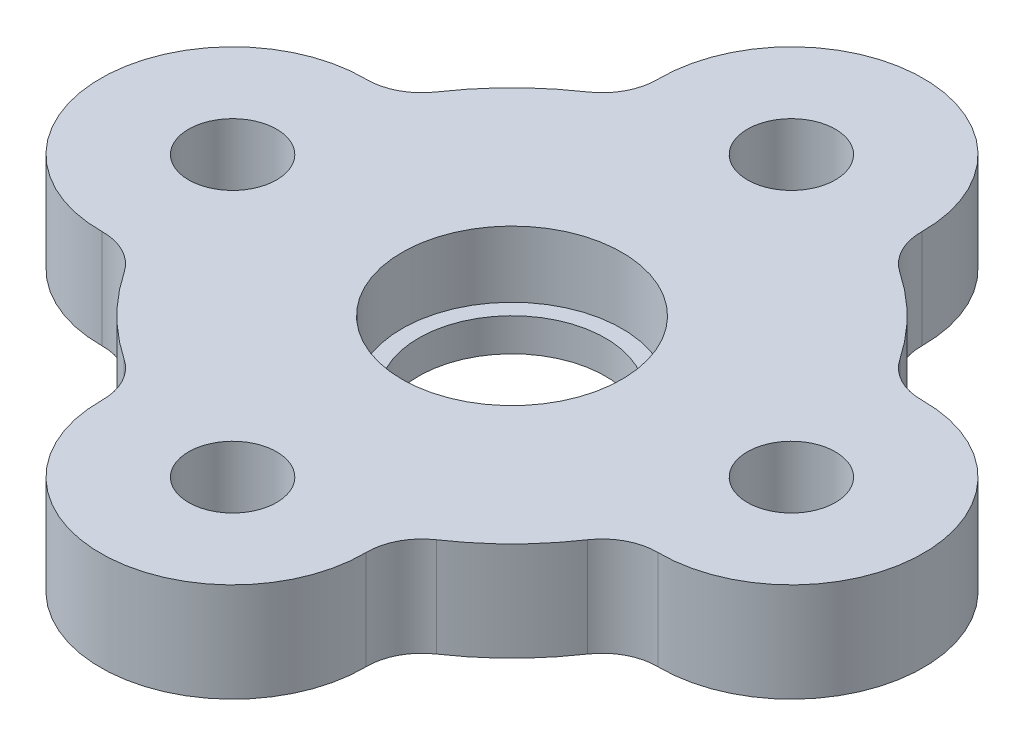
SolidWorks part; units mm, degrees
material "1060 Alloy"
ref_plane "Front" through (0, 0, 0) normal (0, 0, 1) x (1, 0, 0)
ref_plane "Top" through (0, 0, 0) normal (0, 1, 0) x (1, 0, 0)
ref_plane "Right" through (0, 0, 0) normal (1, 0, 0) x (0, 0, -1)
sketch "Sketch1" plane through (0, 0, 0) normal (0, 1, 0) x (1, 0, 0)
  line L0 (0, 0) -> (0, 44.45) construction
  circle A0 centre (-25.4, 0) radius 4
  circle A1 centre (0, 25.4) radius 4
  circle A2 centre (25.4, 0) radius 4
  circle A3 centre (0, -25.4) radius 4
  circle A4 centre (0, 0) radius 8.5
  arc A6 (11.9992, 25.261) -> (-11.9992, 25.261) centre (0, 25.4) ccw
  arc A7 (25.261, -11.9992) -> (25.261, 11.9992) centre (25.4, 0) ccw
  arc A8 (-11.9992, -25.261) -> (11.9992, -25.261) centre (0, -25.4) ccw
  arc A9 (-25.261, 11.9992) -> (-25.261, -11.9992) centre (-25.4, 0) ccw
  arc A10 (-14.203, 21.0579) -> (-21.0579, 14.203) centre (0, 0) ccw
  arc A11 (-21.0579, -14.203) -> (-14.203, -21.0579) centre (0, 0) ccw
  arc A12 (14.203, -21.0579) -> (21.0579, -14.203) centre (0, 0) ccw
  arc A13 (21.0579, 14.203) -> (14.203, 21.0579) centre (0, 0) ccw
  arc A14 (14.203, 21.0579) -> (11.9992, 25.261) centre (16.9989, 25.2031) cw
  arc A15 (25.261, 11.9992) -> (21.0579, 14.203) centre (25.2031, 16.9989) cw
  arc A16 (25.261, -11.9992) -> (21.0579, -14.203) centre (25.2031, -16.9989) ccw
  arc A17 (11.9992, -25.261) -> (14.203, -21.0579) centre (16.9989, -25.2031) cw
  arc A18 (-11.9992, -25.261) -> (-14.203, -21.0579) centre (-16.9989, -25.2031) ccw
  arc A19 (-25.261, -11.9992) -> (-21.0579, -14.203) centre (-25.2031, -16.9989) cw
  arc A20 (-25.261, 11.9992) -> (-21.0579, 14.203) centre (-25.2031, 16.9989) ccw
  arc A21 (-14.203, 21.0579) -> (-11.9992, 25.261) centre (-16.9989, 25.2031) ccw
  point P0 (0, 0)
  point P17 (0, 0)
  point P25 (0, 0)
  point P30 (22.5654, 11.6604)
  point P33 (22.5654, -11.6604)
  point P36 (11.6604, -22.5654)
  point P39 (-11.6604, -22.5654)
  point P42 (-22.5654, -11.6604)
  dimension "D5" = 8
  dimension "D6" = 17
  dimension "D3" = 24
  dimension "D8" = 5
  dimension "D2" = 50.8
  dimension "D4" = 4
  dimension "D7" = 4
extrude "body and center hole" add sketch "Sketch1" along normal blind 9
sketch "Sketch2" plane through (0, 9, 0) normal (0, 1, 0) x (1, 0, 0)
  circle A0 centre (0, 0) radius 10
  dimension "D1" = 20
extrude "seal cavity" cut sketch "Sketch2" against normal blind 6
equation "\"D2@Sketch1\"=\"square plate bolt pattern diameter\""
equation "\"D5@Sketch1\"=\"square plate bolt hole ID\""
equation "\"D1@body and center hole\"=\"small seal plate thickness\""
equation "\"D6@Sketch1\"=\"small seal plate lip ID\""
equation "\"D1@Sketch2\"=\"small seal OD\""
equation "\"D1@seal cavity\" = \"small seal depth\""
equation "\"bearing OD\" = 30mm"
equation "\"bearing outer race thickness\"= 1mm"
equation "\"bearing ID\"= 10mm"
equation "\"bearing depth\"= 9mm"
equation "\"bearing inner race thickness\"= 1mm"
equation "\"small seal OD\" = 20mm"
equation "\"small seal ID\"= 8mm"
equation "\"small seal depth\" = 6mm"
equation "\"big seal OD\" = 30mm"
equation "\"big seal ID\"= 15mm"
equation "\"big seal depth\"= 8mm"
equation "\"z\" = 12"
equation "\"de\" = 0.426in"
equation "\"d2\" = 2.097in"
equation "\"d_exit\" =\"b2\""
equation "\"theta\" = 15"
equation "\"b2\" = .15in"
equation "\"b1\" = \"b2\" + (\"d2\"/2 - \"de\"/2)*sin(\"theta\")"
equation "\"s\" = ( 1/\"z\")*(3.14*\"de\" - (3.14*(\"de\"^2) / (4*(\"b1\"))))"
equation "\"s_opening\" = (3.14*\"de\" - \"z\"*\"s\")/\"z\""
equation "\"area_eye\"=3.14*(\"de\"^2)/4"
equation "\"single_channel_area\"=\"s_opening\"*\"b1\""
equation "\"impeller upper clearance\"= .5mm"
equation "\"impeller horizontal clearance\"= .5mm"
equation "\"impeller bottom clearance\"= .5mm"
equation "\"impeller base thickness\"= 2mm"
equation "\"impeller boss depth\" = 14mm"
equation "\"impeller boss diameter\" = \"big seal ID\""
equation "\"impeller dowel diameter\" = 2mm"
equation "\"impeller bolt head diameter\" = 7.5mm"
equation "\"impeller bolt head depth\" = 4mm"
equation "\"impeller shaft bore\"= 8mm"
equation "\"impeller shaft bore depth\" = \"impeller boss depth\" + \"impeller base thickness\" - \"impeller bolt head depth\" - 3mm"
equation "\"impeller dowel length\" = 2mm*2 + \"impeller shaft bore\""
equation "\"impeller screw hole bore\" = 4mm"
equation "\"shaft impeller screw hole diameter\" = \"impeller screw hole bore\""
equation "\"shaft impeller section length\" = \"impeller shaft bore depth\""
equation "\"shaft impeller screw hole depth\" = \"shaft impeller section length\"-\"impeller dowel diameter\"-2mm"
equation "\"shaft impeller section diameter\" = \"impeller shaft bore\""
equation "\"shaft seal section diameter\"=\"small seal ID\""
equation "\"shaft seal section length\"=\"small seal depth\" + 2mm"
equation "\"shaft bearing section diameter\" = \"bearing ID\""
equation "\"shaft bearing section length\" = \"bearing depth\""
equation "\"shaft bearing stop diameter\" = \"bearing ID\" + 2mm"
equation "\"shaft bearing stop length\" = 2mm"
equation "\"shaft coupler section diameter\" = 8mm"
equation "\"shaft coupler section length\" = \"shaft bearing stop length\" + \"coupler length\"/2 + 4mm"
equation "\"coupler set screw drill hole ID\"= 6mm"
equation "\"coupler set screw 1 distance\"= \"motor mount shaft hole depth\" / 3"
equation "\"coupler set screw 2 distance\"= \"motor mount shaft hole depth\" * 4 / 5"
equation "\"coupler motor shaft hole ID\"= 8mm"
equation "\"coupler impeller shaft hole ID\"= \"shaft coupler section diameter\""
equation "\"coupler OD\"= 17mm"
equation "\"coupler length\"= 25mm"
equation "\"square plate diameter\" = 3in"
equation "\"square plate bolt pattern diameter\"= 2in"
equation "\"square plate bolt hole ID\" = 8mm"
equation "\"bearing plate bearing stop ID\" = \"bearing OD\" - 4mm"
equation "\"bearing plate bearing stop depth\" = 3mm"
equation "\"bearing plate thickness\" = \"bearing depth\" + \"bearing plate bearing stop depth\""
equation "\"small seal plate lip depth\" = \"shaft bearing stop length\" + 1mm"
equation "\"small seal plate lip ID\" = \"small seal OD\" - 3mm"
equation "\"small seal plate thickness\" = \"small seal plate lip depth\" + \"small seal depth\""
equation "\"big seal plate lip depth\" = 3mm"
equation "\"big seal plate thickness\" = \"shaft bearing stop length\" + \"shaft seal section length\" + \"impeller boss depth\" - \"impeller bottom clearance\"-\"small seal plate thickness\""
equation "\"impeller cavity center height\"= \"impeller bottom clearance\" + \"impeller upper clearance\" + \"final impeller center height\""
equation "\"impeller cavity diameter\"= 2 * \"impeller horizontal clearance\" + \"d2\""
equation "\"impeller cavity outer height\"= \"impeller bottom clearance\" + \"impeller upper clearance\" + \"impeller base thickness\" + \"b2\""
equation "\"impeller housing bolt count\" = 8"
equation "\"impeller housing bolt diameter\" = 6mm"
equation "\"impeller housing bolt pattern diameter\" = 2.75in"
equation "\"impeller housing o-ring channel height\"= 1.5mm"
equation "\"impeller housing o ring channel width\"= 1.5mm"
equation "\"impeller housing o-ring diameter\" = 2in"
equation "\"impeller housing threaded inlet diameter\" = 14mm"
equation "\"impeller housing threaded inlet depth\"= 8mm"
equation "\"impeller housing thickness\"= \"impeller housing threaded inlet depth\" + \"impeller cavity center height\"+ 4mm"
equation "\"impeller housing exit threaded diameter\"= 8mm"
equation "\"impeller housing exit threaded depth\"= 8mm"
equation "\"impeller housing diameter\" = 3.5in"
equation "\"impeller housing diffuser conical angle\"=10"
equation "\"impeller housing diffuser tangent angle\"=20"
equation "\"impeller housing outlet purchase\" = 5mm"
equation "\"motor to housing distance\" = \"motor shaft pride\" + \"shaft coupler section length\" - \"bearing plate bearing stop depth\" + 2mm"
equation "\"motor mount coupler hole diameter\"= \"coupler OD\"+ 4mm"
equation "\"motor mount to housing post radius\"= ( 3 * \"square plate bolt hole ID\" ) / 2"
equation "\"motor mount m4 screw hole diameter\"= 4mm"
equation "\"motor mount m4 head diameter\"= 7.25mm"
equation "\"motor mount m4 head depth\"= 4mm"
equation "\"motor mount plate thickness\"= 8mm + \"motor mount m4 head depth\""
equation "\"motor shaft pride\"= 32mm"
equation "\"motor shaft flat section length from tip\"= 25.7mm"
equation "\"motor shaft bore end clearance\"= 2mm"
equation "\"coupler shaft to motor clearance\" = 2mm"
equation "\"motor mount shaft hole depth\"= \"motor shaft pride\""
equation "\"D3@Sketch1\"=\"square plate bolt hole ID\"*3"
